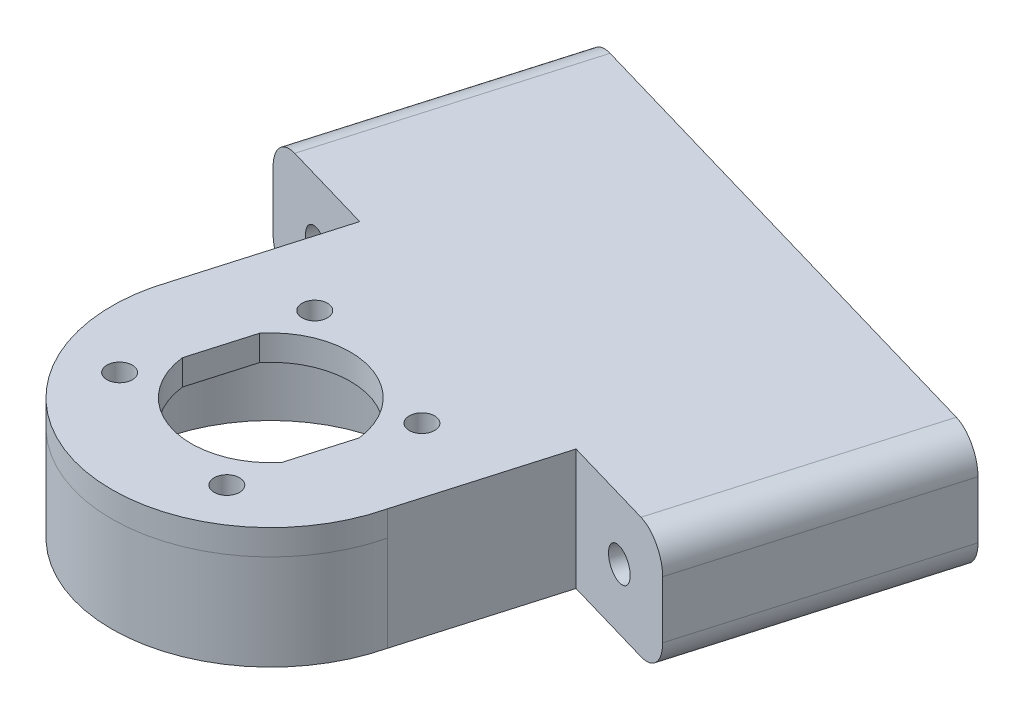
SolidWorks part; units mm, degrees
ref_plane "Front Plane" through (0, 0, 0) normal (0, 0, 1) x (1, 0, 0)
ref_plane "Top Plane" through (0, 0, 0) normal (0, 1, 0) x (1, 0, 0)
ref_plane "Right Plane" through (0, 0, 0) normal (1, 0, 0) x (0, 0, -1)
sketch "Sketch1" plane through (0, 0, 0) normal (0, 1, 0) x (1, 0, 0)
  line L0 (8.8101, -41.586) -> (11.5467, -32.178)
  line L1 (30.8948, -48.0099) -> (33.6314, -38.6018)
  circle A0 centre (29.6465, -55.432) radius 2
  circle A1 centre (36.5588, -31.6681) radius 2
  circle A2 centre (12.7949, -24.7558) radius 2
  circle A3 centre (5.8827, -48.5197) radius 2
  circle A4 centre (21.2207, -40.0939) radius 4
  arc A5 (33.6314, -38.6018) -> (11.5467, -32.178) centre (21.2207, -40.0939) ccw
  circle A6 centre (21.2207, -40.0939) radius 25
  arc A7 (8.8101, -41.586) -> (30.8948, -48.0099) centre (21.2207, -40.0939) ccw
  dimension "D1" = 50
extrude "Boss-Extrude1" add sketch "Sketch1" along normal blind 4 contours A6 A7 L0 A5 L1 A0 A1 A2 A3
sketch "Sketch2" plane through (0, 0, 0) normal (0, -1, 0) x (1, 0, 0)
  circle A0 centre (21.2207, 40.0939) radius 25
  circle A1 centre (21.2207, 40.0939) radius 22.5
  dimension "D2" = 45
  dimension "D1" = 50
extrude "Boss-Extrude2" add sketch "Sketch2" along normal blind 15
ref_plane "Plane1" through (-2.1147, 0, 7.2701) normal (0.2793, 0, -0.9602) x (-0.9602, 0, -0.2793)
sketch "Sketch4" plane through (-2.1147, 0, 7.2701) normal (0.2793, 0, -0.9602) x (-0.9602, 0, -0.2793)
  line L0 (-56.5744, -15) -> (-6.5744, -15) construction
  line L1 (-56.5512, -15) -> (-6.5958, -15)
  line L2 (-56.5512, -15) -> (-56.5512, 4)
  line L3 (-56.5512, 4) -> (-6.5958, 4)
  line L4 (-6.5958, -15) -> (-6.5958, 4)
  line L5 (-6.5744, 4) -> (-56.5744, 4) construction
extrude "Boss-Extrude7" add sketch "Sketch4" against normal up to next
sketch "Sketch5" plane through (-2.1147, 0, 7.2701) normal (0.2793, 0, -0.9602) x (-0.9602, 0, -0.2793)
  line L0 (-56.5512, -5.5) -> (19.3148, -5.5) construction
  line L1 (-56.5512, 4) -> (-56.5512, -15) construction
  line L5 (-76.5512, 4) -> (-76.5512, -15)
  line L6 (-76.5512, 4) -> (-76.5512, -15)
  line L7 (-76.5512, 4) -> (13.4042, 4)
  line L8 (13.4042, -15) -> (13.4042, 4)
  line L9 (13.4042, -15) -> (13.4042, 4)
  line L10 (13.4042, 4) -> (13.3182, 3.7861)
  line L11 (-76.5512, -15) -> (13.4042, -15)
  dimension "D1" = 20
  dimension "D2" = 20
extrude "Boss-Extrude8" add sketch "Sketch5" along normal blind 40
sketch "Sketch7" plane through (9.0572, 0, -31.1381) normal (0.2793, 0, -0.9602) x (-0.9602, 0, -0.2793)
  line L0 (-76.5512, 4) -> (-76.5512, -15) construction
  line L2 (13.4042, -15) -> (13.4042, 4) construction
  line L3 (-76.5512, -15) -> (13.4042, -15) construction
  circle A0 centre (-66.5512, -5.5) radius 2.5
  circle A1 centre (3.4042, -5.5) radius 2.5
  point P8 (13.4042, -5.5)
  dimension "D1" = 5
  dimension "D3" = 5
  dimension "D2" = 10
  dimension "D4" = 10
  dimension "D5" = 69.9554
  dimension "D6" = 9.5
extrude "Cut-Extrude1" cut sketch "Sketch7" against normal through all
fillet "Fillet1" radius 5 1 edges at (76.9761, -15, 9.4467)
fillet "Fillet2" radius 5 3 edges at (-9.3995, 4, -15.6777) (-9.3995, -15, -15.6777) (76.9761, 4, 9.4467)
